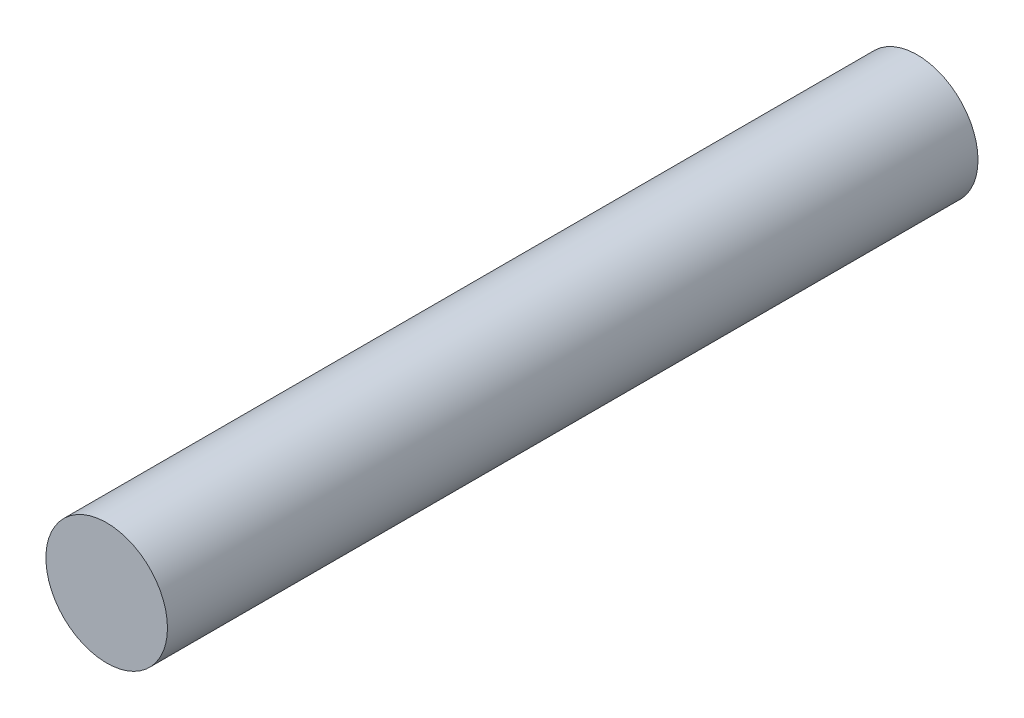
SolidWorks part; units mm, degrees
ref_plane "Plano frontal" through (0, 0, 0) normal (0, 0, 1) x (1, 0, 0)
ref_plane "Plano superior" through (0, 0, 0) normal (0, 1, 0) x (1, 0, 0)
ref_plane "Plano direito" through (0, 0, 0) normal (1, 0, 0) x (0, 0, -1)
sketch "Esboço1" plane through (0, 0, 0) normal (0, 0, 1) x (1, 0, 0)
  circle A0 centre (0, 0) radius 1.5
  dimension "D1" = 3
extrude "Ressalto-extrusão1" add sketch "Esboço1" along normal blind 20
